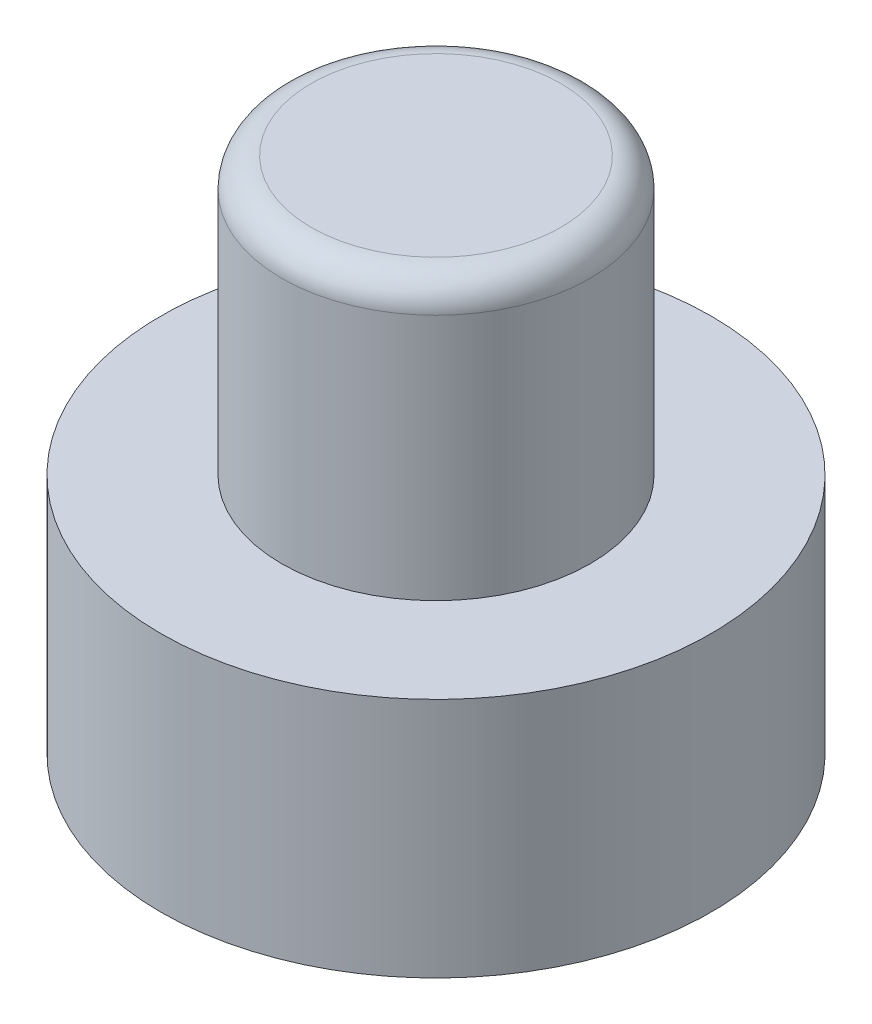
SolidWorks part; units mm, degrees
ref_plane "Front Plane" through (0, 0, 0) normal (0, 0, 1) x (1, 0, 0)
ref_plane "Top Plane" through (0, 0, 0) normal (0, 1, 0) x (1, 0, 0)
ref_plane "Right Plane" through (0, 0, 0) normal (1, 0, 0) x (0, 0, -1)
sketch "Sketch1" plane through (0, 0, 0) normal (0, 1, 0) x (1, 0, 0)
  circle A0 centre (0, 0) radius 4.675
  dimension "D1" = 9.35
extrude "Boss-Extrude1" add sketch "Sketch1" along normal blind 4.1
sketch "Sketch2" plane through (0, 4.1, 0) normal (0, 1, 0) x (1, 0, 0)
  circle A0 centre (0, 0) radius 2.62
  dimension "D1" = 5.24
extrude "Boss-Extrude2" add sketch "Sketch2" along normal blind 4.7
fillet "Fillet1" radius 0.5 1 edges at (0, 8.8, 2.62)
